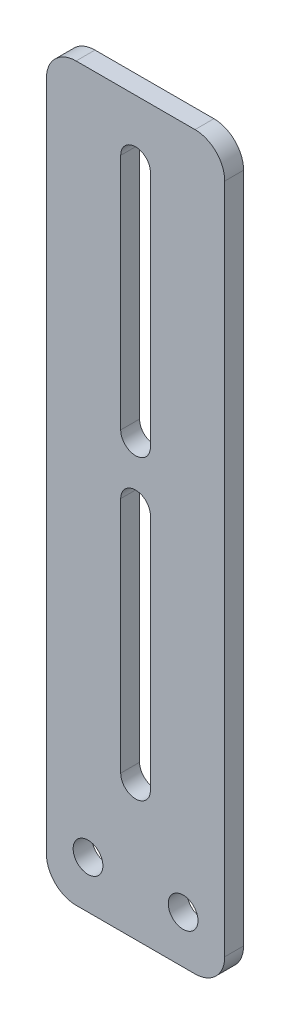
SolidWorks part; units mm, degrees
ref_plane "Front Plane" through (0, 0, 0) normal (0, 0, 1) x (1, 0, 0)
ref_plane "Top Plane" through (0, 0, 0) normal (0, 1, 0) x (1, 0, 0)
ref_plane "Right Plane" through (0, 0, 0) normal (1, 0, 0) x (0, 0, -1)
sketch "Sketch1" plane through (0, 0, 0) normal (0, 0, 1) x (1, 0, 0)
  line L0 (-15, 123) -> (-15, 0)
  line L9 (0, 113) -> (0, 23) construction
  line L10 (2.5, 113) -> (2.5, 73)
  line L16 (-15, 0) -> (15, 0)
  line L17 (15, 0) -> (15, 123)
  line L18 (0, 123) -> (0, 0) construction
  line L25 (-2.5, 113) -> (-2.5, 73)
  line L26 (-8, 8) -> (8, 8) construction
  line L28 (-15, 123) -> (15, 123)
  line L29 (-30.3829, 68) -> (30.3829, 68) construction
  line L32 (0, 73) -> (0, 63) construction
  line L33 (-2.5, 63) -> (-2.5, 23)
  line L34 (2.5, 63) -> (2.5, 23)
  circle A11 centre (-8, 8) radius 2.5
  circle A12 centre (8, 8) radius 2.5
  arc A23 (2.5, 113) -> (-2.5, 113) centre (0, 113) ccw
  arc A24 (-2.5, 23) -> (2.5, 23) centre (0, 23) ccw
  arc A25 (-2.5, 73) -> (2.5, 73) centre (0, 73) ccw
  arc A26 (-2.5, 63) -> (2.5, 63) centre (0, 63) cw
  point P7 (0, 68)
  point P26 (0, 73)
  point P27 (0, 63)
  point P32 (0, 68)
  dimension "D6" = 5
  dimension "D7" = 8
  dimension "D2" = 5
  dimension "D3" = 10
  dimension "D1" = 30
  dimension "D4" = 15
  dimension "D5" = 16
  dimension "D8" = 40
  dimension "D9" = 50
extrude "Boss-Extrude1" add sketch "Sketch1" along normal blind 3.175
fillet "Fillet2" radius 5 4 edges at (15, 0, 1.5875) (-15, 0, 1.5875) (15, 123, 1.5875) (-15, 123, 1.5875)
